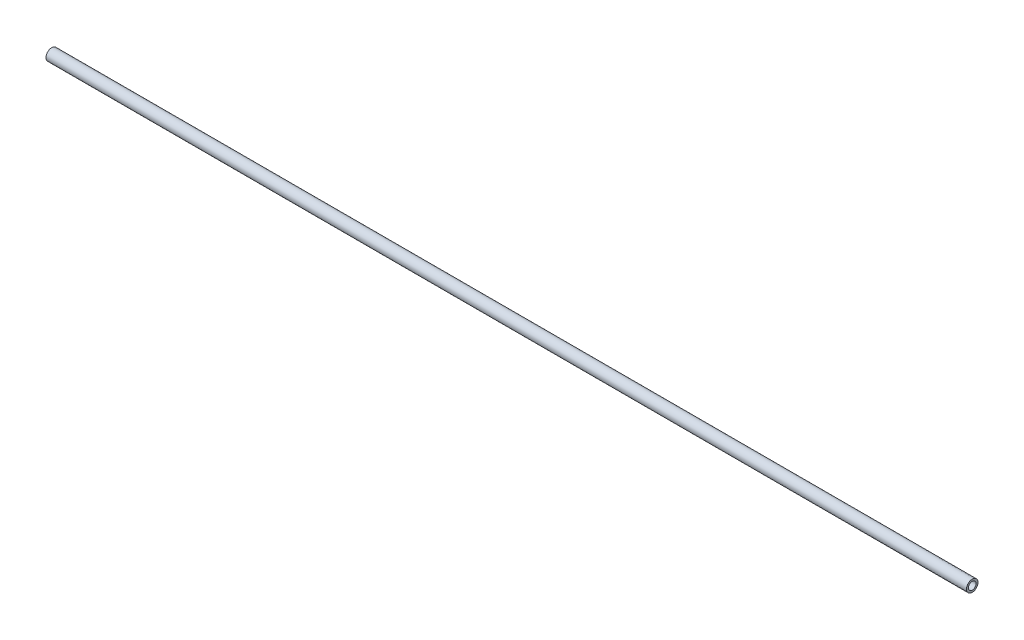
SolidWorks part; units mm, degrees
ref_plane "Front" through (0, 0, 0) normal (0, 0, 1) x (1, 0, 0)
ref_plane "Top" through (0, 0, 0) normal (0, 1, 0) x (1, 0, 0)
ref_plane "Right" through (0, 0, 0) normal (1, 0, 0) x (0, 0, -1)
sketch "Sketch1" plane through (0, 0, 0) normal (1, 0, 0) x (0, 0, -1)
  circle A0 centre (0, 0) radius 9.525
  circle A1 centre (0, 0) radius 6.35
  point P4 (9.525, 0)
  point P5 (6.35, 0)
  dimension "OD" = 19.05
  dimension "ID" = 12.7
  dimension "Wall" = 3.175
extrude "Extrude1" add sketch "Sketch1" along normal mid plane 1524
